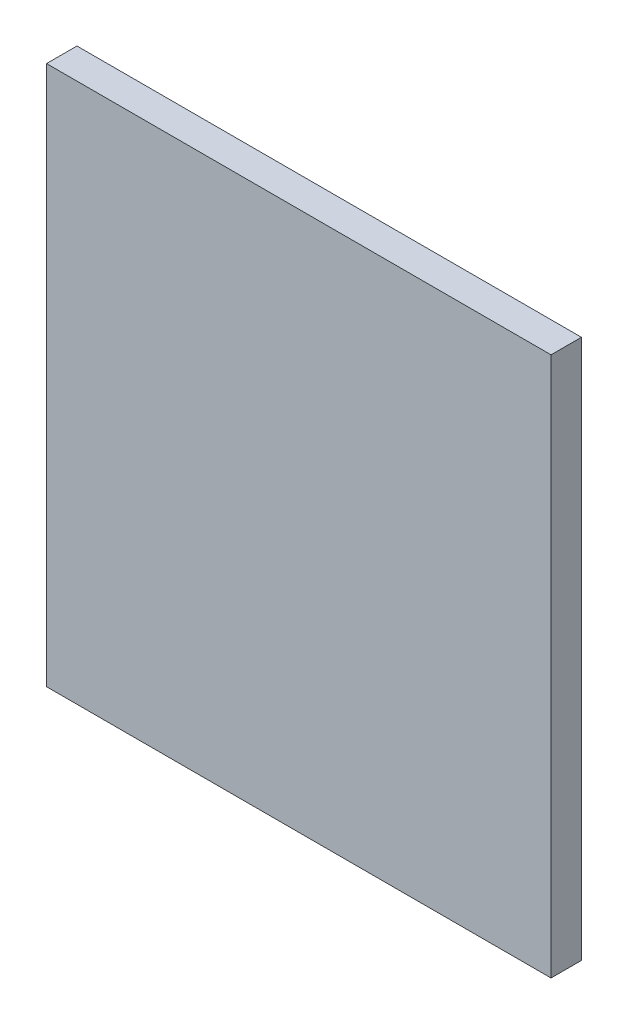
SolidWorks part; units mm, degrees
ref_plane "前视基准面" through (0, 0, 0) normal (0, 0, 1) x (1, 0, 0)
ref_plane "上视基准面" through (0, 0, 0) normal (0, 1, 0) x (1, 0, 0)
ref_plane "右视基准面" through (0, 0, 0) normal (1, 0, 0) x (0, 0, -1)
sketch "草图1" plane through (0, 0, 0) normal (0, 0, 1) x (1, 0, 0)
  line L0 (0, 0) -> (15.76, 0)
  line L1 (15.76, 0) -> (15.76, 33.72)
  line L2 (15.76, 33.72) -> (-15.76, 33.72)
  line L3 (-15.76, 33.72) -> (-15.76, 0)
  line L4 (-15.76, 0) -> (0, 0)
  dimension "D1" = 31.52
  dimension "D2" = 33.72
extrude "凸台-拉伸1" add sketch "草图1" along normal blind 1.9
sketch "草图2" plane through (0, 0, 0) normal (0, -1, 0) x (1, 0, 0)
  line L2 (-15.76, 1.9) -> (15.76, 1.9) construction
  line L3 (0, 1.9) -> (5.7, 1.9)
  line L4 (5.7, 1.9) -> (5.7, 1.77)
  line L5 (5.7, 1.77) -> (-5.7, 1.77)
  line L6 (-5.7, 1.77) -> (-5.7, 1.9)
  line L7 (-5.7, 1.9) -> (0, 1.9)
  dimension "D1" = 11.4
  dimension "D2" = 0.13
